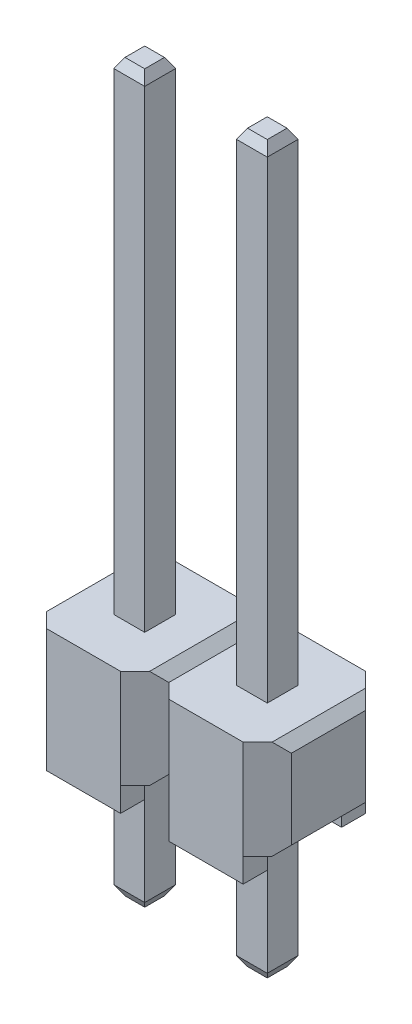
SolidWorks part; units mm, degrees
ref_plane "Front Plane" through (0, 0, 0) normal (0, 0, 1) x (1, 0, 0)
ref_plane "Top Plane" through (0, 0, 0) normal (0, 1, 0) x (1, 0, 0)
ref_plane "Right Plane" through (0, 0, 0) normal (1, 0, 0) x (0, 0, -1)
sketch "Sketch1" plane through (0, 0, 0) normal (0, 1, 0) x (1, 0, 0)
  line L0 (-2.04, -1.27) -> (-0.5, -1.27)
  line L1 (0, -0.77) -> (-0.5, -1.27)
  line L2 (0.5, -1.27) -> (2.04, -1.27)
  line L3 (-55, 0) -> (55, 0) construction
  line L4 (-2.54, 0) -> (-1.59, 0) construction
  line L5 (-1.59, 0) -> (-0.95, 0) construction
  line L6 (-0.95, 0) -> (0.95, 0) construction
  line L7 (0.95, 0) -> (1.59, 0) construction
  line L8 (1.59, 0) -> (2.54, 0) construction
  line L9 (-1.27, 1.27) -> (-1.27, 0.32) construction
  line L10 (-1.27, 0.32) -> (-1.27, -0.32) construction
  line L11 (-1.27, -0.32) -> (-1.27, -1.27) construction
  line L12 (0, 0.77) -> (0, 0) construction
  line L13 (0, 0) -> (0, -0.77) construction
  line L22 (1.59, -0.32) -> (1.59, 0.32)
  line L34 (0, -55) -> (0, 55) construction
  line L44 (-2.04, 1.27) -> (-0.5, 1.27)
  line L45 (-0.5, 1.27) -> (0, 0.77)
  line L46 (-1.59, -0.32) -> (-1.59, 0.32)
  line L47 (0.95, -0.32) -> (1.59, -0.32)
  line L48 (2.54, 0.77) -> (2.54, -0.77)
  line L49 (-2.04, -1.27) -> (-2.54, -0.77)
  line L51 (-1.59, -0.32) -> (-0.95, -0.32)
  line L53 (0, 0.77) -> (0.5, 1.27)
  line L54 (2.54, -0.77) -> (2.04, -1.27)
  line L55 (2.04, 1.27) -> (2.54, 0.77)
  line L56 (0.95, 0.32) -> (1.59, 0.32)
  line L57 (-2.54, 0.77) -> (-2.04, 1.27)
  line L58 (-2.54, -0.77) -> (-2.54, 0.77)
  line L59 (-1.59, 0.32) -> (-0.95, 0.32)
  line L60 (-0.95, -0.32) -> (-0.95, 0.32)
  line L61 (0.5, -1.27) -> (0, -0.77)
  line L62 (0.5, 1.27) -> (2.04, 1.27)
  line L63 (0.95, -0.32) -> (0.95, 0.32)
  dimension "D1" = 5.08
  dimension "D2" = 2.54
  dimension "D3" = 1.27
  dimension "D4" = 2.54
  dimension "D5" = 0.64
  dimension "D7" = 0.5
  dimension "D10" = 0.5
  dimension "D11" = 1.54
extrude "Boss-Extrude1" add sketch "Sketch1" against normal blind 2.05
sketch "Sketch2" plane through (0, 0, 0) normal (0, 0, 1) x (1, 0, 0)
  line L0 (-2.54, -0.2) -> (-2.54, 0)
  line L3 (-2.54, -2.05) -> (-2.54, 0) construction
  line L4 (-2.54, 0) -> (-2.34, 0)
  line L5 (-2.54, 0) -> (-2.04, 0) construction
  line L8 (-2.34, 0) -> (-2.54, -0.2)
  line L10 (-0.2, 0) -> (0.2, 0)
  line L11 (-0.5, 0) -> (0, 0) construction
  line L13 (0, 0) -> (0.5, 0) construction
  line L15 (0.2, 0) -> (0, -0.2)
  line L16 (0, -2.05) -> (0, 0) construction
  line L17 (0, -0.2) -> (-0.2, 0)
  line L18 (2.34, 0) -> (2.54, 0)
  line L19 (2.04, 0) -> (2.54, 0) construction
  line L20 (2.54, 0) -> (2.54, -0.2)
  line L21 (2.54, -2.05) -> (2.54, 0) construction
  line L22 (2.54, -0.2) -> (2.34, 0)
  line L23 (-2.54, -1.85) -> (-2.34, -2.05)
  line L24 (-2.54, -2.05) -> (-2.04, -2.05) construction
  line L25 (-2.34, -2.05) -> (-2.54, -2.05)
  line L26 (-2.54, -2.05) -> (-2.54, -1.85)
  line L27 (-0.2, -2.05) -> (0, -1.85)
  line L28 (-0.5, -2.05) -> (0, -2.05) construction
  line L29 (0, -1.85) -> (0.2, -2.05)
  line L31 (0.2, -2.05) -> (-0.2, -2.05)
  line L32 (2.34, -2.05) -> (2.54, -1.85)
  line L34 (2.54, -1.85) -> (2.54, -2.05)
  line L35 (2.54, -2.05) -> (2.34, -2.05)
  dimension "D1" = 0.2
  dimension "D2" = 0.4
extrude "Cut-Extrude1" cut sketch "Sketch2" against normal mid plane 10
sketch "Sketch3" plane through (0, -2.05, 0) normal (0, -1, 0) x (1, 0, 0)
  line L2 (-2.04, -1.27) -> (-0.5, -1.27)
  line L3 (-2.04, -1.27) -> (-2.04, -0.77)
  line L4 (-2.04, -0.77) -> (-0.5, -0.77)
  line L5 (-0.5, -1.27) -> (-0.5, -0.77)
  line L6 (-0.5, 1.27) -> (-2.04, 1.27)
  line L7 (-0.5, 1.27) -> (-0.5, 0.77)
  line L8 (-0.5, 0.77) -> (-2.04, 0.77)
  line L9 (-2.04, 1.27) -> (-2.04, 0.77)
  line L10 (0.5, 1.27) -> (2.04, 1.27)
  line L11 (0.5, 1.27) -> (0.5, 0.77)
  line L12 (0.5, 0.77) -> (2.04, 0.77)
  line L13 (2.04, 1.27) -> (2.04, 0.77)
  line L14 (2.04, -1.27) -> (0.5, -1.27)
  line L15 (2.04, -1.27) -> (2.04, -0.77)
  line L16 (2.04, -0.77) -> (0.5, -0.77)
  line L17 (0.5, -1.27) -> (0.5, -0.77)
  dimension "D1" = 0.5
extrude "Boss-Extrude2" add sketch "Sketch3" along normal blind 0.5
sketch "Sketch4" plane through (0, 0, 0) normal (0, 1, 0) x (1, 0, 0)
  line L1 (-1.59, 0.32) -> (-0.95, 0.32)
  line L2 (-1.59, 0.32) -> (-1.59, -0.32)
  line L3 (-1.59, -0.32) -> (-0.95, -0.32)
  line L4 (-0.95, 0.32) -> (-0.95, -0.32)
  line L5 (0.95, 0.32) -> (1.59, 0.32)
  line L6 (0.95, 0.32) -> (0.95, -0.32)
  line L7 (0.95, -0.32) -> (1.59, -0.32)
  line L8 (1.59, 0.32) -> (1.59, -0.32)
extrude "Boss-Extrude3" add sketch "Sketch4" along normal blind 10 and the other way offset from surface (5.05 mm away) 3 other way up to face at (1.27, -2.05, 0)
chamfer "Chamfer1" distance 0.2 angle 30 16 edges at (-1.27, -5.05, 0.32) (-0.95, -5.05, 0) (-1.27, -5.05, -0.32) (-1.59, -5.05, 0) (1.27, -5.05, 0.32) (1.59, -5.05, 0) (1.27, -5.05, -0.32) (0.95, -5.05, 0) (1.27, 10, -0.32) (1.59, 10, 0) (1.27, 10, 0.32) (0.95, 10, 0) (-1.27, 10, -0.32) (-0.95, 10, 0) (-1.27, 10, 0.32) (-1.59, 10, 0)
sketch "Sketch5" plane through (0, -5.05, 0) normal (0, -1, 0) x (1, 0, 0)
  line L0 (-1.59, 0) -> (-0.95, 0) construction
  line L1 (-1.59, -0.32) -> (-1.59, 0.32) construction
  line L2 (-0.95, 0.32) -> (-0.95, -0.32) construction
  circle A0 centre (-1.27, 0) radius 0.125
  dimension "D1" = 0.25
extrude "Cut-Extrude2" cut sketch "Sketch5" against normal blind 1
